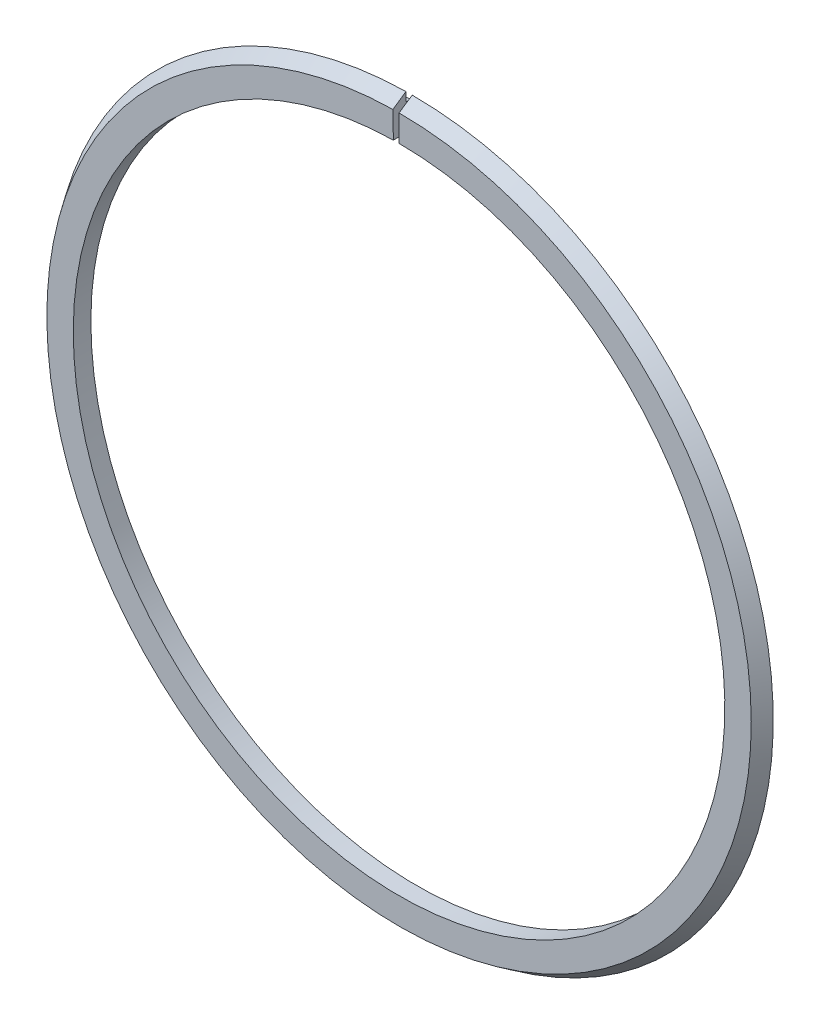
SolidWorks part; units mm, degrees
ref_plane "前视基准面" through (0, 0, 0) normal (0, 0, 1) x (1, 0, 0)
ref_plane "上视基准面" through (0, 0, 0) normal (0, 1, 0) x (1, 0, 0)
ref_plane "右视基准面" through (0, 0, 0) normal (1, 0, 0) x (0, 0, -1)
other "Configuration Table"
sketch "草图2" plane through (0, 0, 0) normal (-1, 0, 0) x (0, 1, 0)
  line L1 (37, 0) -> (40, 0)
  line L2 (37, 0) -> (37, 2)
  line L3 (0, 0) -> (0, 9.2768) construction
  line L4 (40, 0) -> (41, 1.5)
  line L5 (40, 1.5) -> (41, 1.5)
  line L6 (40, 1.5) -> (40, 2)
  line L7 (40, 2) -> (37, 2)
  line L8 (0, 9.2768) -> (0, -10.2865) construction
  dimension "D1" = 3
  dimension "D2" = 4
  dimension "D3" = 2
  dimension "D4" = 0.5
  dimension "D5" = 37
  dimension "D6" = 40
revolve "旋转2" add sketch "草图2" angle 359 about L3
